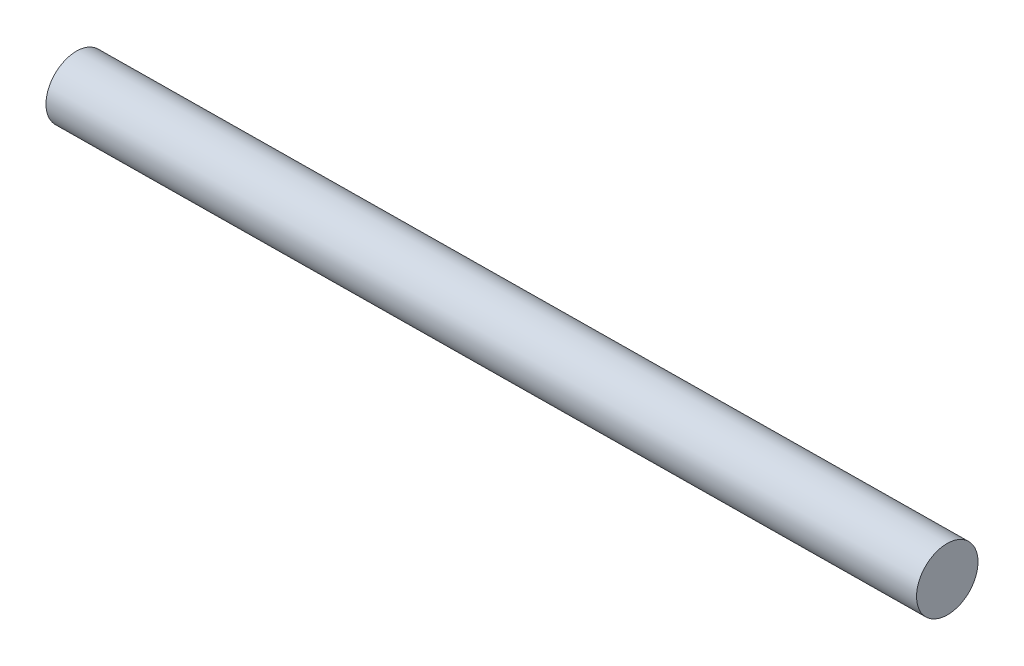
SolidWorks part; units mm, degrees
ref_plane "Front Plane" through (0, 0, 0) normal (0, 0, 1) x (1, 0, 0)
ref_plane "Top Plane" through (0, 0, 0) normal (0, 1, 0) x (1, 0, 0)
ref_plane "Right Plane" through (0, 0, 0) normal (1, 0, 0) x (0, 0, -1)
sketch "Sketch1" plane through (0, 0, 0) normal (0, 0, 1) x (1, 0, 0)
  line L0 (0, 0) -> (255, 2.5984)
  line L1 (127.5, 1.2992) -> (127.5, 19.5657) construction
  dimension "D1" = 255
sweep "Sweep1" add path "Sketch1" circular profile diameter 18 parameters "D3"=18
